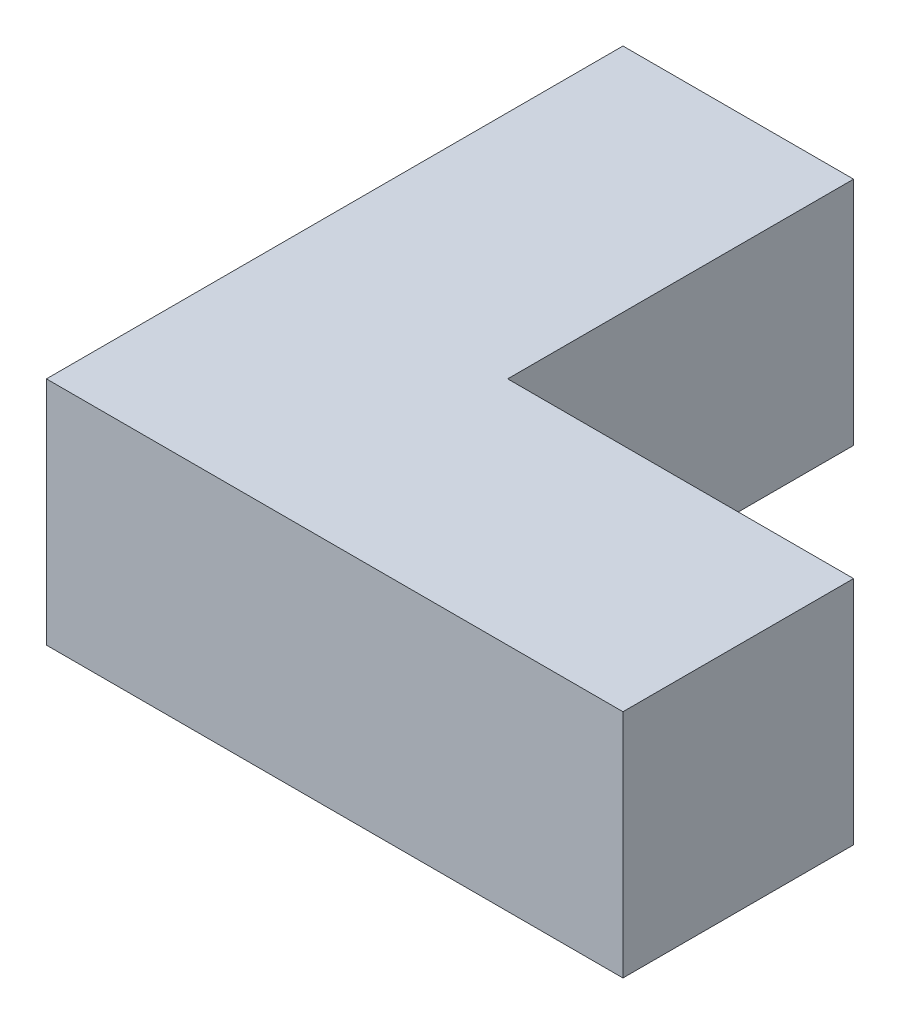
SolidWorks part; units mm, degrees
ref_plane "Front Plane" through (0, 0, 0) normal (0, 0, 1) x (1, 0, 0)
ref_plane "Top Plane" through (0, 0, 0) normal (0, 1, 0) x (1, 0, 0)
ref_plane "Right Plane" through (0, 0, 0) normal (1, 0, 0) x (0, 0, -1)
sketch "Sketch1" plane through (0, 0, 0) normal (0, 1, 0) x (1, 0, 0)
  line L0 (0, 0) -> (25, 0)
  line L1 (0, 0) -> (0, 10)
  line L2 (25, 0) -> (25, 10)
  line L3 (0, 10) -> (25, 10)
  line L4 (0, 0) -> (0, 25)
  line L5 (0, 0) -> (10, 0)
  line L6 (0, 0) -> (0, 25)
  line L7 (0, 25) -> (10, 25)
  line L8 (10, 0) -> (10, 25)
  line L9 (10, 25) -> (10, 10)
  line L10 (10, 10) -> (25, 10)
  line L11 (25, 0) -> (0, 0)
  dimension "D1" = 10
  dimension "D2" = 25
  dimension "D3" = 25
  dimension "D4" = 10
extrude "Boss-Extrude2" add sketch "Sketch1" against normal blind 10 contours L8 L0 L2 L3 | L0 L8 L3 L1 | L3 L8 L7 L4
sketch "Sketch4" plane through (0, 0, 0) normal (0, 0, 1) x (1, 0, 0)
  line L0 (25, -10) -> (25, -6.4445)
  line L1 (25, -10) -> (25, 0) construction
